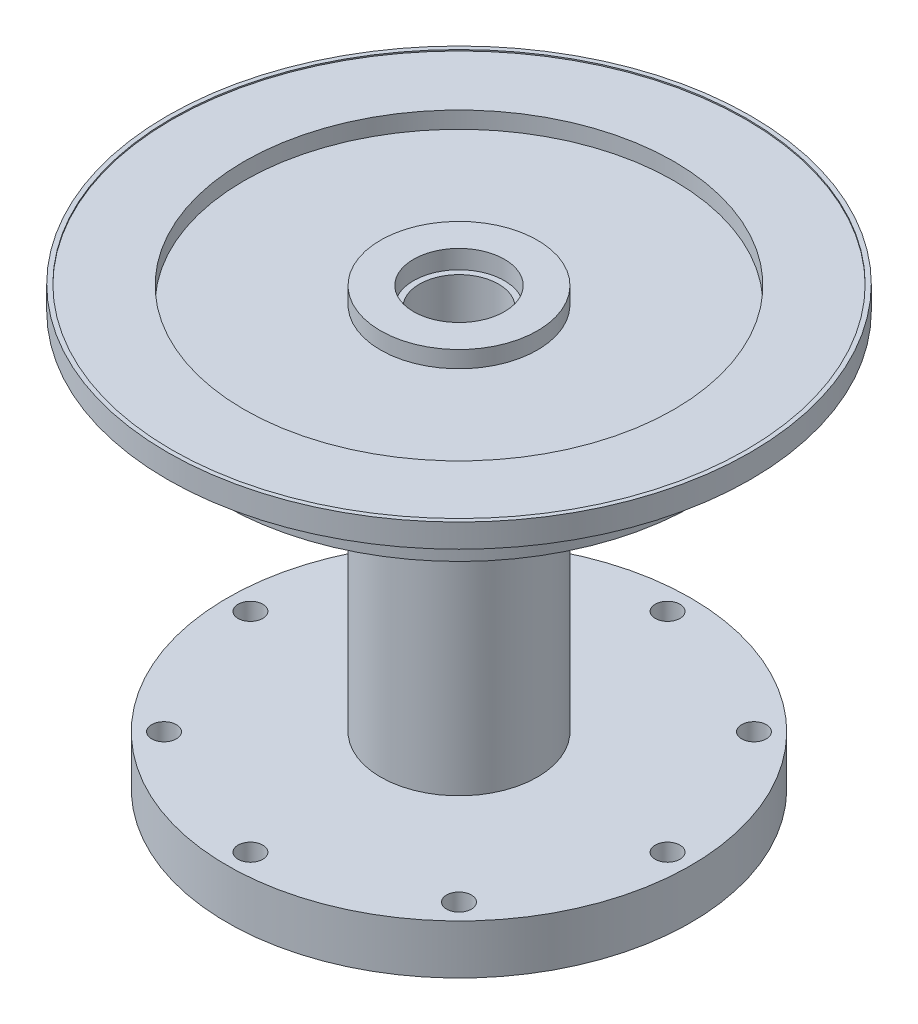
SolidWorks part; units mm, degrees
material "AISI 316 Stainless Steel Sheet (SS)"
ref_plane "Front Plane" through (0, 0, 0) normal (0, 0, 1) x (1, 0, 0)
ref_plane "Top Plane" through (0, 0, 0) normal (0, 1, 0) x (1, 0, 0)
ref_plane "Right Plane" through (0, 0, 0) normal (1, 0, 0) x (0, 0, -1)
sketch "Sketch1" plane through (0, 0, 0) normal (0, 1, 0) x (1, 0, 0)
  circle A0 centre (0, 0) radius 38.1
  dimension "D1" = 76.2
extrude "Boss-Extrude1" add sketch "Sketch1" along normal blind 4.826
sketch "Sketch2" plane through (0, 4.826, 0) normal (0, 1, 0) x (1, 0, 0)
  circle A0 centre (0, 0) radius 38.1 construction
  circle A1 centre (0, 0) radius 38.1
extrude "Boss-Extrude2" add sketch "Sketch2" along normal blind 3.302 draft 70 draft outward yes
sketch "Sketch3" plane through (0, 8.128, 0) normal (0, 1, 0) x (1, 0, 0)
  circle A0 centre (0, 0) radius 47.1722 construction
  circle A1 centre (0, 0) radius 47.1722
extrude "Boss-Extrude3" add sketch "Sketch3" along normal blind 3.81
sketch "Sketch4" plane through (0, 11.938, 0) normal (0, 1, 0) x (1, 0, 0)
  circle A3 centre (0, 0) radius 46.4722
  circle A4 centre (0, 0) radius 46.4722
  dimension "D1" = 0.7
extrude "Cut-Extrude1" cut sketch "Sketch4" against normal blind 0.2
sketch "Sketch6" plane through (0, 11.738, 0) normal (0, 1, 0) x (1, 0, 0)
  circle A1 centre (0, 0) radius 12.7
  circle A2 centre (0, 0) radius 34.7722
  circle A3 centre (0, 0) radius 34.7722
  dimension "D2" = 25.4
  dimension "D1" = 11.7
extrude "Cut-Extrude2" cut sketch "Sketch6" against normal blind 2.7
sketch "Sketch7" plane through (0, 11.738, 0) normal (0, 1, 0) x (1, 0, 0)
  circle A0 centre (0, 0) radius 5.35
  dimension "D1" = 10.7
sketch "Sketch8" plane through (0, 0, 0) normal (0, -1, 0) x (1, 0, 0)
  circle A1 centre (0, 0) radius 12.7
  circle A3 centre (0, 0) radius 12.7
  dimension "D1" = 0
extrude "Boss-Extrude4" add sketch "Sketch8" along normal blind 50.8
sketch "Sketch10" plane through (0, 11.738, 0) normal (0, 1, 0) x (1, 0, 0)
  circle A0 centre (0, 0) radius 7.35
  dimension "D1" = 14.7
extrude "Cut-Extrude5" cut sketch "Sketch10" against normal blind 3
sketch "Sketch11" plane through (0, 0, 0) normal (0, -1, 0) x (1, 0, 0)
  circle A0 centre (0, 0) radius 6.4
  dimension "D1" = 12.8
ref_plane "Plane2" through (0, -50.8, 0) normal (0, -1, 0) x (-1, 0, 0)
sketch "Sketch13" plane through (0, -50.8, 0) normal (0, -1, 0) x (-1, 0, 0)
  circle A0 centre (0, 0) radius 6.4 construction
  circle A1 centre (0, 0) radius 6.4
extrude "Cut-Extrude9" cut sketch "Sketch13" against normal through all
sketch "Sketch15" plane through (0, -50.8, 0) normal (0, -1, 0) x (1, 0, 0)
  circle A1 centre (0, 0) radius 37.5
  circle A2 centre (0, 0) radius 37.5
  dimension "D1" = 0
extrude "Boss-Extrude6" add sketch "Sketch15" along normal blind 8
sketch "Sketch16" plane through (0, -58.8, 0) normal (0, -1, 0) x (1, 0, 0)
  circle A0 centre (0, 0) radius 5.35 construction
  circle A1 centre (0, 33.75) radius 2
  circle A2 centre (0, 33.75) radius 2
  circle A3 centre (23.8649, 23.8649) radius 2
  circle A4 centre (23.8649, 23.8649) radius 2
  circle A5 centre (33.75, 0) radius 2
  circle A6 centre (33.75, 0) radius 2
  circle A7 centre (23.8649, -23.8649) radius 2
  circle A8 centre (23.8649, -23.8649) radius 2
  circle A9 centre (0, -33.75) radius 2
  circle A10 centre (0, -33.75) radius 2
  circle A11 centre (-23.8649, -23.8649) radius 2
  circle A12 centre (-23.8649, -23.8649) radius 2
  circle A13 centre (-33.75, 0) radius 2
  circle A14 centre (-33.75, 0) radius 2
  circle A15 centre (-23.8649, 23.8649) radius 2
  circle A16 centre (-23.8649, 23.8649) radius 2
  circle A17 centre (0, 0) radius 5.35
  dimension "D1" = 0
  dimension "D2" = 0
  dimension "D3" = 0
  dimension "D4" = 0
  dimension "D5" = 0
  dimension "D6" = 0
  dimension "D7" = 0
  dimension "D8" = 0
extrude "Cut-Extrude10" cut sketch "Sketch16" against normal up to next
sketch "Sketch17" plane through (0, -58.8, 0) normal (0, -1, 0) x (1, 0, 0)
  circle A0 centre (0, 0) radius 19.21 construction
  circle A1 centre (0, 0) radius 20.71 construction
  circle A2 centre (0, 0) radius 19.21
  circle A3 centre (0, 0) radius 20.71
extrude "Cut-Extrude11" cut sketch "Sketch17" against normal blind 3
